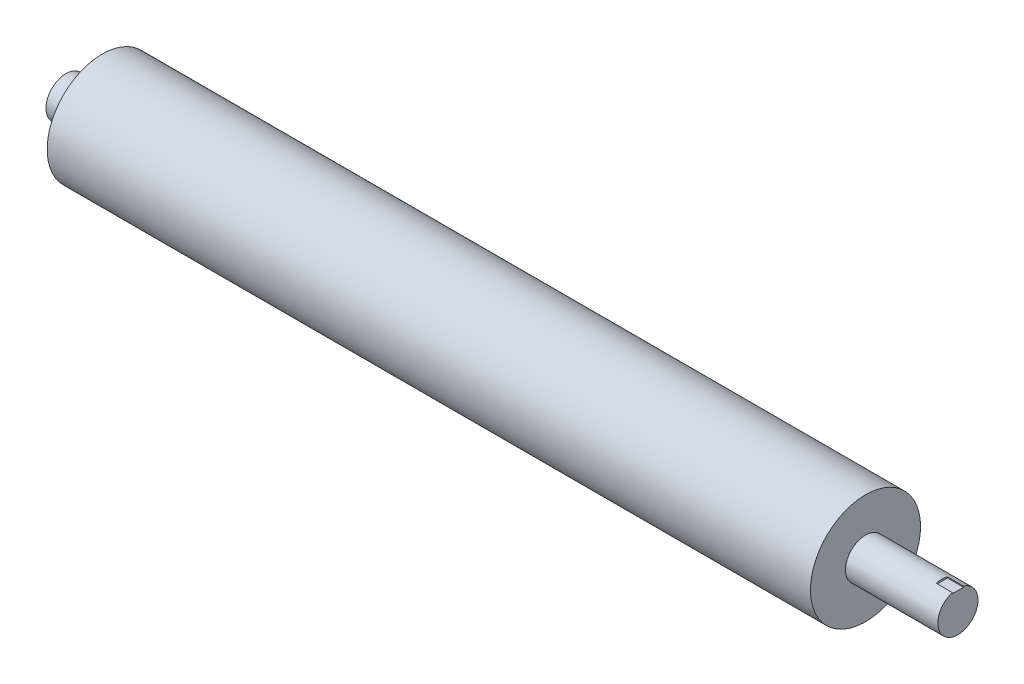
SolidWorks part; units mm, degrees
ref_plane "Front Plane" through (0, 0, 0) normal (0, 0, 1) x (1, 0, 0)
ref_plane "Top Plane" through (0, 0, 0) normal (0, 1, 0) x (1, 0, 0)
ref_plane "Right Plane" through (0, 0, 0) normal (1, 0, 0) x (0, 0, -1)
sketch "Sketch1" plane through (0, 0, 0) normal (0, 1, 0) x (1, 0, 0)
  line L0 (0, 0) -> (0, 461.25) construction
  line L1 (0, 0) -> (-1040, 0)
  line L2 (-1040, 0) -> (-1040, 50)
  line L3 (-1040, 50) -> (-950, 50)
  line L4 (-950, 50) -> (-950, 137)
  line L5 (-950, 137) -> (0, 137)
  line L7 (1180, 50) -> (950, 50)
  line L8 (950, 50) -> (950, 137)
  line L9 (950, 137) -> (0, 137)
  line L10 (0, 0) -> (1180, 0)
  line L11 (1180, 0) -> (1180, 50)
  point P3 (1147.6571, 50)
  dimension "D1" = 90
  dimension "D2" = 950
  dimension "D3" = 230
  dimension "D4" = 1900
  dimension "D5" = 50
  dimension "D6" = 50
revolve "Revolve1" add sketch "Sketch1" angle 360 about L1
sketch "Sketch2" plane through (1180, 0, 0) normal (1, 0, 0) x (0, 0, -1)
  line L0 (0, 0) -> (0, 48) construction
  line L1 (-14, 48) -> (14, 48) construction
  line L2 (14, 45.4) -> (-14, 45.4)
  line L3 (14, 45.4) -> (14, 50.6)
  line L4 (14, 50.6) -> (-14, 50.6)
  line L5 (-14, 45.4) -> (-14, 50.6)
  line L6 (14, 45.4) -> (-14, 50.6) construction
  line L7 (14, 50.6) -> (-14, 45.4) construction
  circle A0 centre (0, 0) radius 50 construction
  dimension "D1" = 28
  dimension "D2" = 2.6
extrude "Cut-Extrude1" cut sketch "Sketch2" against normal blind 40
